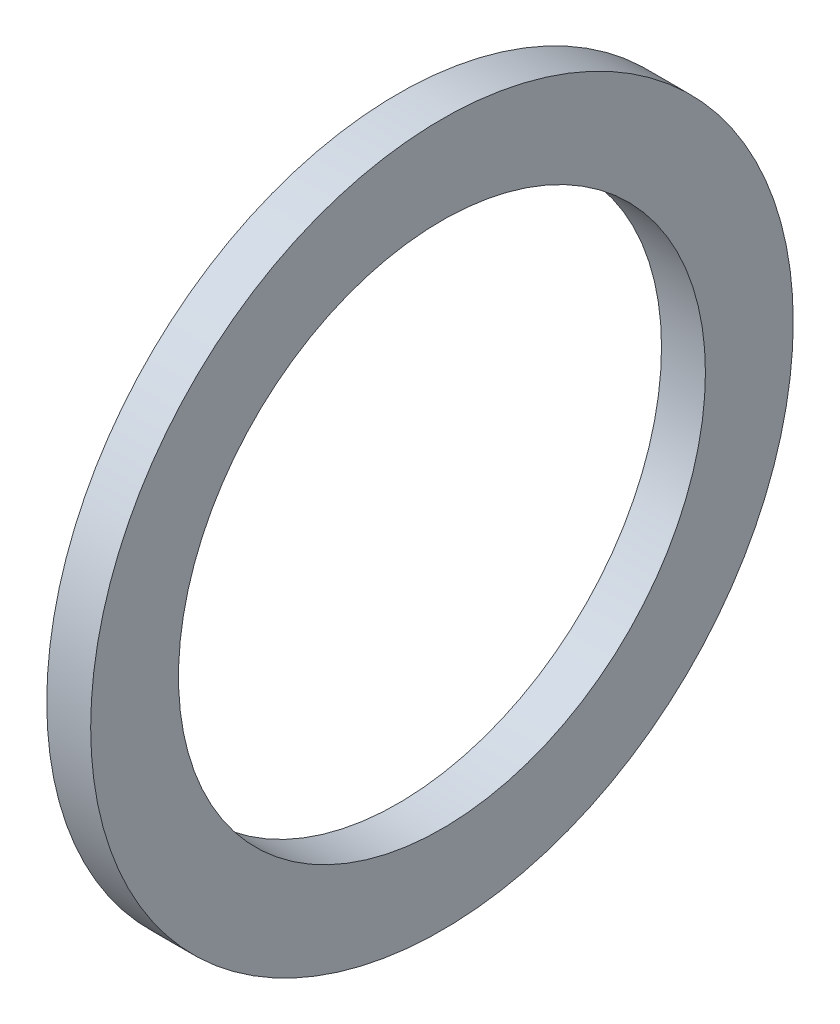
SolidWorks part; units mm, degrees
material "6061-T6 (SS)"
ref_plane "Front Plane" through (0, 0, 0) normal (0, 0, 1) x (1, 0, 0)
ref_plane "Top Plane" through (0, 0, 0) normal (0, 1, 0) x (1, 0, 0)
ref_plane "Right Plane" through (0, 0, 0) normal (1, 0, 0) x (0, 0, -1)
sketch "Sketch1" plane through (0, 0, 0) normal (1, 0, 0) x (0, 0, -1)
  circle A0 centre (0, 0) radius 9.525
  circle A1 centre (0, 0) radius 12.7
  dimension "D1" = 19.05
  dimension "D2" = 25.4
extrude "Boss-Extrude1" add sketch "Sketch1" along normal blind 1.5875
